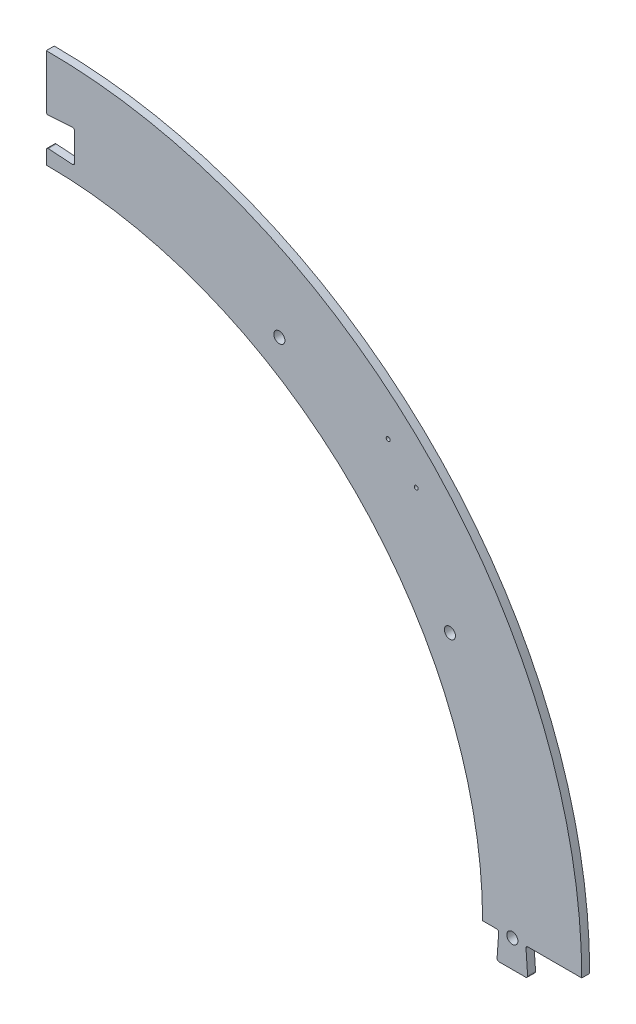
SolidWorks part; units mm, degrees
ref_plane "Front Plane" through (0, 0, 0) normal (0, 0, 1) x (1, 0, 0)
ref_plane "Top Plane" through (0, 0, 0) normal (0, 1, 0) x (1, 0, 0)
ref_plane "Right Plane" through (0, 0, 0) normal (1, 0, 0) x (0, 0, -1)
sketch "Sketch1" plane through (0, 0, 0) normal (0, 0, 1) x (1, 0, 0)
  circle A0 centre (0, 0) radius 125
  dimension "D1" = 250
sketch "Sketch2" plane through (0, 0, 0) normal (0, 0, 1) x (1, 0, 0)
  line L0 (0, 135) -> (0, 110)
  line L1 (110, 0) -> (135, 0)
  arc A0 (0, 135) -> (135, 0) centre (0, 0) cw
  arc A1 (0, 110) -> (110, 0) centre (0, 0) cw
  dimension "D1" = 135
  dimension "D2" = 110
extrude "Boss-Extrude1" add sketch "Sketch2" along normal blind 2
sketch "Sketch3" plane through (0, 0, 0) normal (0, 0, -1) x (-1, 0, 0)
  line L0 (-110, 0) -> (-135, 0) construction
  line L1 (0, 135) -> (0, 110) construction
  line L2 (0, 125.8) -> (0, 125)
  line L3 (-125.8, 0) -> (-125, 0)
  arc A0 (-125, 0) -> (0, 125) centre (0, 0) cw
  circle A1 centre (0, 0) radius 125 construction
  arc A2 (-125.8, 0) -> (0, 125.8) centre (0, 0) cw
  dimension "D1" = 0.8
extrude "Boss-Extrude2" add sketch "Sketch3" along normal blind 2
sketch "Sketch5" plane through (0, 0, 0) normal (0, 0, 1) x (1, 0, 0)
  line L0 (114, 0) -> (113.5, -7)
  line L1 (110, 0) -> (135, 0) construction
  line L2 (113.5, -7) -> (121.5, -7)
  line L3 (121.5, -7) -> (121, 0)
  line L4 (121, 0) -> (114, 0)
  line L5 (110, 0) -> (125, 0) construction
  line L6 (0, 121) -> (0, 114)
  line L7 (0, 114) -> (7, 113.5)
  line L8 (7, 113.5) -> (7, 121.5)
  line L9 (7, 121.5) -> (0, 121)
  line L10 (0, 135) -> (0, 110) construction
  point P10 (117.5, 0)
  point P17 (0, 0)
  dimension "D1" = 8
  dimension "D2" = 7
  dimension "D3" = 7
  dimension "D4" = 2
sketch "Sketch7" plane through (0, 0, 0) normal (0, 0, 1) x (1, 0, 0)
  line L14 (121, 0) -> (114, 0) construction
  line L15 (114.1003, 0) -> (120.8997, 0)
  line L16 (113.6074, -6.9) -> (121.3926, -6.9)
  line L17 (114.0997, -0.0071) -> (113.6074, -6.9)
  line L18 (121.3926, -6.9) -> (120.9003, -0.0071)
  line L19 (113.6074, -6.9) -> (121.3926, -6.9)
  line L20 (114.1003, 0) -> (113.6074, -6.9)
  line L21 (121.3926, -6.9) -> (120.8997, 0)
  dimension "D1" = 0.1
extrude "Boss-Extrude3" add sketch "Sketch7" along normal up to surface (2 mm away) up to face at (73.9353, 73.9353, 2)
sketch "Sketch8" plane through (0, 0, 2) normal (0, 0, 1) x (1, 0, 0)
  line L9 (-0.0071, 121.0997) -> (-0.0071, 113.9003)
  line L12 (-0.0071, 113.9003) -> (7.1, 113.3926)
  line L13 (7.1, 113.3926) -> (7.1, 121.6074)
  line L14 (7.1, 121.6074) -> (-0.0071, 121.0997)
  line L15 (-0.0071, 113.9003) -> (7.1, 113.3926)
  line L16 (7.1, 113.3926) -> (7.1, 121.6074)
  line L17 (7.1, 121.6074) -> (-0.0071, 121.0997)
  dimension "D1" = 0.1
extrude "Cut-Extrude1" cut sketch "Sketch8" against normal up to next
fillet "Fillet1" radius 0.5 8 edges at (120.8997, 0, 1) (121.3926, -6.9, 1) (113.6074, -6.9, 1) (114.1003, 0, 1) (0, 113.8997, 1) (0, 121.1003, 1) (7.1, 113.3926, 1) (7.1, 121.6074, 1)
sketch "Sketch4" plane through (0, 0, 0) normal (0, 0, 1) x (1, 0, 0)
  line L0 (0, 135) -> (0, 121.6372) construction
  line L1 (110, 0) -> (113.5633, 0) construction
  line L2 (0, 125) -> (0, 110) construction
  line L3 (0, 0) -> (58.75, 101.758) construction
  line L4 (0, 0) -> (101.758, 58.75) construction
  line L5 (0, 0) -> (117.5, 0) construction
  arc A0 (0, 117.5) -> (117.5, 0) centre (0, 0) cw construction
  arc A1 (110, 0) -> (0, 110) centre (0, 0) ccw construction
  circle A2 centre (58.75, 101.758) radius 1.4
  circle A3 centre (101.758, 58.75) radius 1.4
  circle A4 centre (117.5, 0) radius 1.4
  point P16 (0, 117.5)
  dimension "D1" = 2.8
  dimension "D2" = 30
  dimension "D3" = 30
extrude "Cut-Extrude3" cut sketch "Sketch4" along normal up to next
sketch "Sketch9" plane through (0, 0, 0) normal (0, 0, -1) x (-1, 0, 0)
  line L0 (0, 135) -> (0, 125.8) construction
  line L1 (-125.8, 0) -> (-135, 0) construction
  line L2 (0, 0) -> (-89.8026, 89.8026) construction
  arc A0 (-127, 0) -> (0, 127) centre (0, 0) cw construction
  circle A1 centre (-93.2685, 86.1974) radius 0.5
  circle A2 centre (-86.1974, 93.2685) radius 0.5
  dimension "D1" = 1
  dimension "D3" = 127
  dimension "D2" = 10
extrude "Cut-Extrude4" cut sketch "Sketch9" against normal up to next
